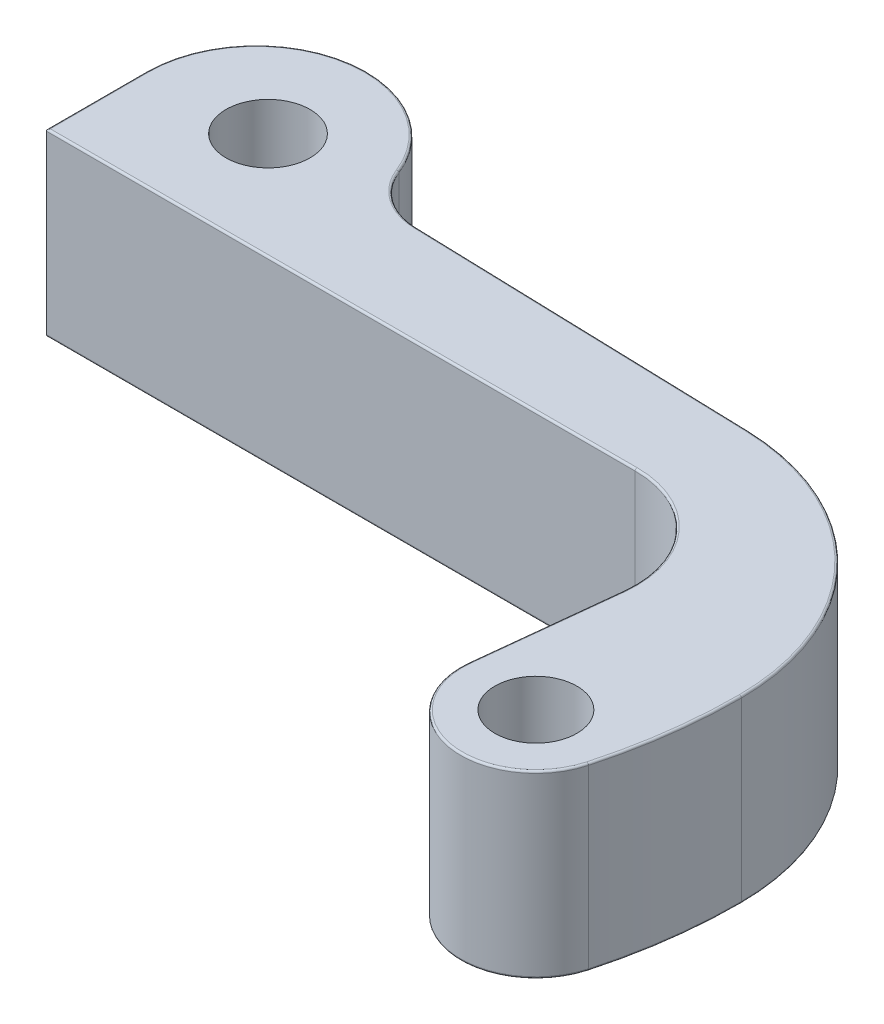
SolidWorks part; units mm, degrees
material "1060 Сплав"
ref_plane "Спереди" through (0, 0, 0) normal (0, 0, 1) x (1, 0, 0)
ref_plane "Сверху" through (0, 0, 0) normal (0, 1, 0) x (1, 0, 0)
ref_plane "Справа" through (0, 0, 0) normal (1, 0, 0) x (0, 0, -1)
sketch "Эскиз1" plane through (0, 0, 0) normal (0, 1, 0) x (1, 0, 0)
  line L0 (0, 0) -> (58.8498, 0)
  line L1 (68.7908, -11.0845) -> (67.2727, -25)
  line L2 (26.9299, 10) -> (61.1239, 8.9878)
  line L3 (0, 0) -> (0, 10)
  arc A0 (21.2446, 14.006) -> (0, 10) centre (11, 10) ccw
  arc A1 (61.1239, 8.9878) -> (83.8183, -14.3406) centre (60.4319, -14.3885) cw
  arc A2 (83.8183, -14.3406) -> (82.0049, -27.8194) centre (33.5841, -14.4434) cw
  arc A3 (68.7908, -11.0845) -> (58.8498, 0) centre (58.8498, -10) ccw
  arc A4 (67.2727, -25) -> (82.0049, -27.8194) centre (74.7524, -25.816) ccw
  circle A5 centre (74.7524, -25.816) radius 4.1
  arc A6 (21.2446, 14.006) -> (26.9299, 10) centre (27.1165, 16.302) ccw
  circle A7 centre (11.5, 10.6629) radius 4.2
  point P15 (70, 0)
  dimension "D1" = 70
  dimension "D3" = 10
  dimension "D5" = 11.5
  dimension "D2" = 8.2
  dimension "D6" = 11
  dimension "D4" = 25
  dimension "D7" = 10
  dimension "D8" = 10
extrude "Бобышка-Вытянуть1" add sketch "Эскиз1" along normal blind 18
fillet "Скругление1" radius 0.2 20 edges at (0, 0, -5) (8.9617, 0, -20.8095) (23.4849, 0, -11.1482) (44.0269, 0, -9.4939) (77.1948, 0, -1.9189) (83.3698, 0, 21.1417) (73.3381, 0, 33.2059) (68.0318, 0, 18.0422) (66.2944, 0, 3.3234) (0, 18, -5) (8.9617, 18, -20.8095) (23.4849, 18, -11.1482) (44.0269, 18, -9.4939) (77.1948, 18, -1.9189) (83.3698, 18, 21.1417) (73.3381, 18, 33.2059) (68.0318, 18, 18.0422) (66.2944, 18, 3.3234) (29.4249, 0, 0) (29.4249, 18, 0)
